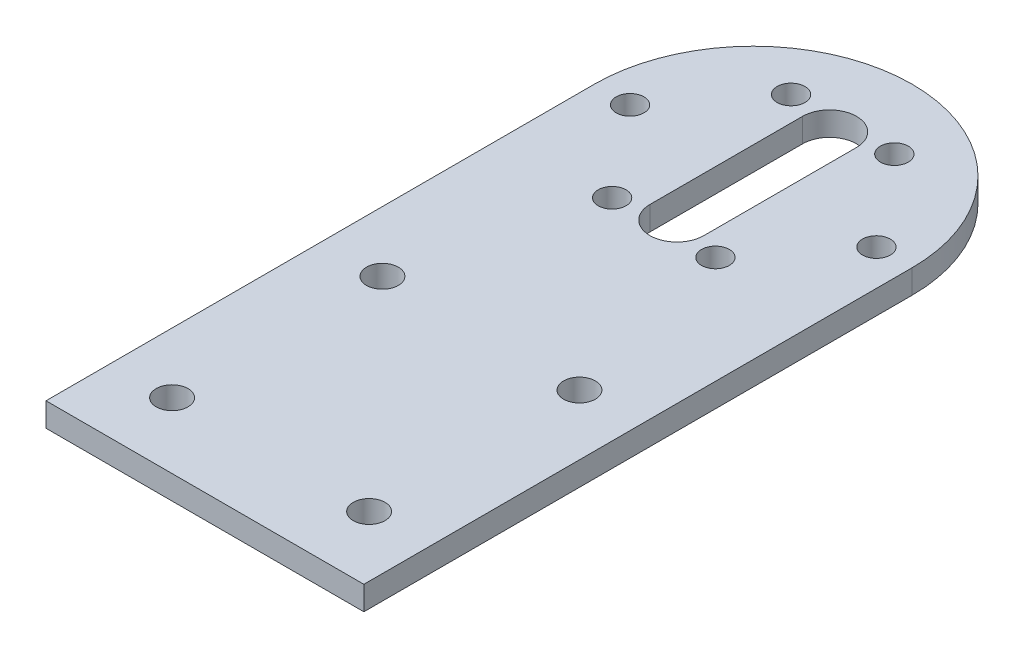
SolidWorks part; units mm, degrees
ref_plane "前视基准面" through (0, 0, 0) normal (0, 0, 1) x (1, 0, 0)
ref_plane "上视基准面" through (0, 0, 0) normal (0, 1, 0) x (1, 0, 0)
ref_plane "右视基准面" through (0, 0, 0) normal (1, 0, 0) x (0, 0, -1)
sketch "草图1" plane through (0, 0, 0) normal (0, 1, 0) x (1, 0, 0)
  line L0 (-20, 0) -> (-20, -69)
  line L1 (-20, -69) -> (20, -69)
  line L2 (20, -69) -> (20, 0)
  line L3 (0, 20) -> (-57.1523, 20) construction
  line L4 (-6.5, 11.2583) -> (6.5, 11.2583) construction
  line L5 (-15.5, 0) -> (15.5, 0) construction
  line L6 (0, 11.2583) -> (0, -69) construction
  line L7 (-6.5, 11.2583) -> (0, 0) construction
  line L8 (-6.5, 11.2583) -> (-6.5, -11.2583) construction
  line L9 (-20, -26) -> (20, -26) construction
  line L10 (-4.6931, -26) -> (-4.6931, -69) construction
  line L11 (-20, -47.5) -> (20, -47.5) construction
  line L12 (0, 9.6052) -> (0, -9.6052) construction
  line L13 (3.3948, 9.6052) -> (3.3948, -9.6052)
  line L14 (-3.3948, 9.6052) -> (-3.3948, -9.6052)
  arc A0 (20, 0) -> (-20, 0) centre (0, 0) ccw
  circle A1 centre (-6.5, 11.2583) radius 1.75
  circle A2 centre (6.5, 11.2583) radius 1.75
  circle A3 centre (-15.5, 0) radius 1.75
  circle A4 centre (15.5, 0) radius 1.75
  circle A5 centre (-6.5, -11.2583) radius 1.75
  circle A6 centre (6.5, -11.2583) radius 1.75
  circle A7 centre (-12.3981, -34.265) radius 2
  circle A8 centre (-12.3981, -60.735) radius 2
  circle A9 centre (12.3981, -34.265) radius 2
  circle A10 centre (12.3981, -60.735) radius 2
  arc A11 (3.3948, 9.6052) -> (-3.3948, 9.6052) centre (0, 9.6052) ccw
  arc A12 (-3.3948, -9.6052) -> (3.3948, -9.6052) centre (0, -9.6052) ccw
  point P22 (0, 0)
  point P23 (-6.5, 0)
  point P36 (-4.6931, -47.5)
  point P38 (0, 0)
  dimension "D1" = 40
  dimension "D3" = 3.5
  dimension "D8" = 4
  dimension "D2" = 89
  dimension "D4" = 13
  dimension "D5" = 31
  dimension "D6" = 60
  dimension "D7" = 43
extrude "凸台-拉伸1" add sketch "草图1" along normal blind 3
